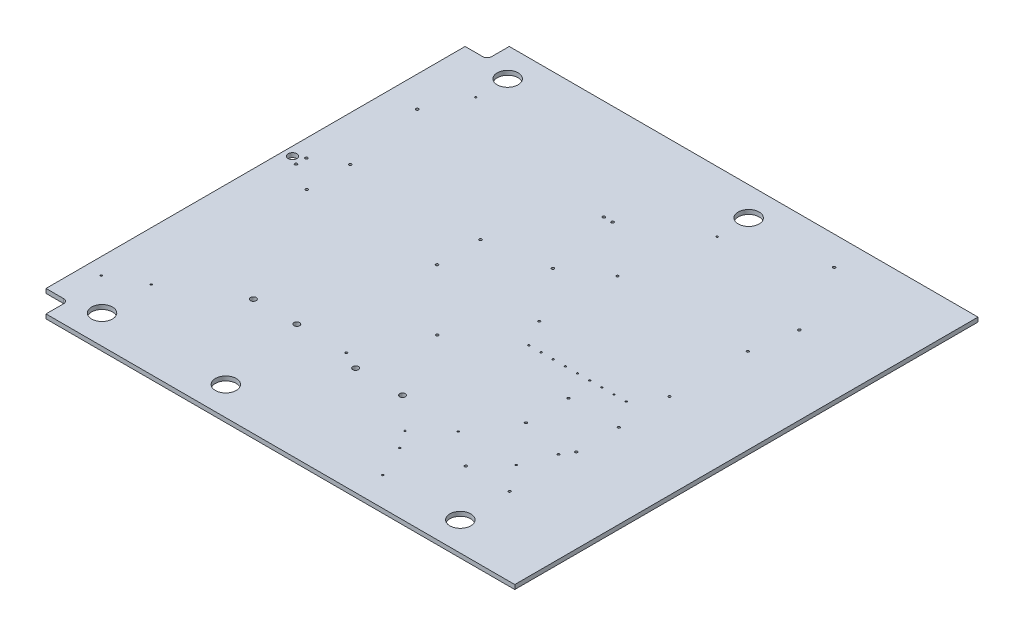
SolidWorks part; units mm, degrees
ref_plane "Front Plane" through (0, 0, 0) normal (0, 0, 1) x (1, 0, 0)
ref_plane "Top Plane" through (0, 0, 0) normal (0, 1, 0) x (1, 0, 0)
ref_plane "Right Plane" through (0, 0, 0) normal (1, 0, 0) x (0, 0, -1)
sketch "Sketch1" plane through (0, 0, 0) normal (1, 0, 0) x (0, 0, -1)
  line L0 (0, 0) -> (-533.4, 0)
  line L1 (-533.4, 0) -> (-533.4, 5)
  line L2 (-533.4, 5) -> (0, 5)
  line L6 (0, 5) -> (0, 0)
  dimension "D1" = 533.4
extrude "Boss-Extrude1" add sketch "Sketch1" along normal blind 565.15
sketch "BotthomHoles-Sketch2" plane through (0, 5, 0) normal (0, 1, 0) x (1, 0, 0)
  line L1 (565.15, 0) -> (565.15, -533.4) construction
  line L2 (565.15, -533.4) -> (0, -533.4) construction
  line L3 (565.15, 0) -> (0, 0) construction
  line L4 (0, 0) -> (0, -533.4) construction
  circle A0 centre (334.275, -33.175) radius 12
  circle A25 centre (199.275, -500.225) radius 12
  circle A26 centre (469.275, -500.225) radius 12
  circle A27 centre (56.75, -500.225) radius 12
  circle A28 centre (56.75, -33.175) radius 12
  dimension "D10" = 24
  dimension "D2" = 95.875
  dimension "D3" = 270
  dimension "D4" = 135
  dimension "D5" = 33.175
  dimension "D6" = 33.175
  dimension "D8" = 500.225
  dimension "D7" = 199.275
  dimension "D9" = 334.275
  dimension "D11" = 469.275
  dimension "D12" = 56.75
extrude "BottomStepperHoles-Cut-Extrude1" cut sketch "BotthomHoles-Sketch2" against normal through all
sketch "BottomPSUHolesSketch2" plane through (0, 5, 0) normal (0, 1, 0) x (1, 0, 0)
  line L0 (0, 0) -> (0, -533.4) construction
  line L1 (565.15, -533.4) -> (0, -533.4) construction
  line L2 (565.15, 0) -> (0, 0) construction
  circle A0 centre (201.5, -209.2) radius 1.5
  circle A1 centre (201.5, -259.2) radius 1.5
  circle A2 centre (51.5, -209.2) radius 1.5
  circle A3 centre (51.5, -259.2) radius 1.5
  circle A6 centre (180, -399.2) radius 3.25
  circle A7 centre (130, -399.2) radius 3.25
  circle A8 centre (257.75, -409.2) radius 3.25
  circle A9 centre (311.75, -409.2) radius 3.25
  dimension "D6" = 3
  dimension "D4" = 6.5
  dimension "D3" = 51.5
  dimension "D1" = 150
  dimension "D2" = 50
  dimension "D7" = 209.2
  dimension "D5" = 50
  dimension "D8" = 140
  dimension "D10" = 134.2
  dimension "D11" = 274.2
  dimension "D12" = 324.2
  dimension "D13" = 201.5
  dimension "D14" = 54
  dimension "D15" = 77.75
  dimension "D16" = 10
  dimension "D9" = 78.5
  dimension "D17" = 130
  dimension "D18" = 124.2
  dimension "D19" = 257.75
  dimension "D20" = 311.75
extrude "BottomPSUHolesCut-Extrude1" cut sketch "BottomPSUHolesSketch2" against normal through all
sketch "OctopusHolesSketch2" plane through (0, 5, 0) normal (0, 1, 0) x (1, 0, 0)
  line L0 (0, 0) -> (0, -533.4) construction
  line L1 (565.15, -533.4) -> (0, -533.4) construction
  circle A0 centre (316.75, -256.7) radius 1.35
  circle A1 centre (466.75, -256.7) radius 1.35
  circle A2 centre (316.75, -166.7) radius 1.35
  circle A3 centre (466.75, -166.7) radius 1.35
  dimension "D1" = 150
  dimension "D3" = 2.7
  dimension "D2" = 90
  dimension "D4" = 115.25
  dimension "D5" = 42.5
  dimension "D6" = 316.75
  dimension "D7" = 466.75
  dimension "D8" = 276.7
  dimension "D9" = 366.7
extrude "OctopusMountHolesCut-Extrude1" cut sketch "OctopusHolesSketch2" against normal through all
sketch "PowrCableGuideMountHolesSketch2" plane through (0, 5, 0) normal (0, 1, 0) x (1, 0, 0)
  line L0 (0, 0) -> (0, -533.4) construction
  line L1 (565.15, -533.4) -> (0, -533.4) construction
  circle A0 centre (271.75, -329.2) radius 1.5
  circle A1 centre (271.75, -196.2) radius 1.5
  dimension "D2" = 3
  dimension "D1" = 133
  dimension "D3" = 45
  dimension "D5" = 271.75
  dimension "D6" = 337.2
  dimension "D7" = 204.2
  dimension "D4" = 29.5
extrude "PowerCableGuideMountHolesCut-Extrude1" cut sketch "PowrCableGuideMountHolesSketch2" against normal through all
sketch "RPIHolesSketch2" plane through (0, 5, 0) normal (0, 1, 0) x (1, 0, 0)
  line L0 (0, 0) -> (0, -533.4) construction
  line L1 (565.15, -533.4) -> (0, -533.4) construction
  circle A4 centre (468.25, -316.7) radius 1.35
  circle A5 centre (468.25, -365.7) radius 1.35
  circle A6 centre (410.25, -316.7) radius 1.35
  circle A7 centre (410.25, -365.7) radius 1.35
  point P4 (282.575, -533.4)
  dimension "D7" = 2.7
  dimension "D1" = 58
  dimension "D2" = 49
  dimension "D3" = 60
  dimension "D4" = 1.5
  dimension "D5" = 410.25
  dimension "D6" = 468.25
  dimension "D8" = 167.7
  dimension "D9" = 216.7
extrude "RPIMountHolesCut-Extrude1" cut sketch "RPIHolesSketch2" against normal through all
sketch "DragChainAndCableGuideHolesSketch2" plane through (0, 5, 0) normal (0, 1, 0) x (1, 0, 0)
  line L3 (565.15, -533.4) -> (0, -533.4) construction
  line L9 (0, 0) -> (0, -533.4) construction
  circle A11 centre (260, -115.65) radius 1.5
  circle A12 centre (10, -234.2) radius 5
  circle A17 centre (475, -115.65) radius 1.5
  circle A18 centre (250, -115.65) radius 1.5
  circle A19 centre (35, -115.65) radius 1.5
  circle A20 centre (20, -240.2) radius 1.5
  circle A21 centre (20, -228.2) radius 1.5
  dimension "D17" = 3
  dimension "D10" = 10
  dimension "D26" = 3
  dimension "D13" = 299.2
  dimension "D15" = 260
  dimension "D5" = 215
  dimension "D16" = 8.25
  dimension "D18" = 475
  dimension "D19" = 215
  dimension "D20" = 10
  dimension "D22" = 35
  dimension "D23" = 250
  dimension "D6" = 25
  dimension "D11" = 10
  dimension "D21" = 6
  dimension "D24" = 6
  dimension "D25" = 20
  dimension "D3" = 417.75
extrude "CragChainAndCableGuideHolesCut-Extrude1" cut sketch "DragChainAndCableGuideHolesSketch2" against normal through all
sketch "Sketch2" plane through (0, 5, 0) normal (0, 1, 0) x (1, 0, 0)
  line L0 (565.15, -533.4) -> (0, -533.4) construction
  line L1 (0, 0) -> (0, -533.4) construction
  circle A0 centre (334.75, -286.7) radius 1
  circle A1 centre (348.75, -286.7) radius 1
  circle A2 centre (362.75, -286.7) radius 1
  circle A3 centre (376.75, -286.7) radius 1
  circle A4 centre (390.75, -286.7) radius 1
  circle A5 centre (404.75, -286.7) radius 1
  circle A6 centre (418.75, -286.7) radius 1
  circle A7 centre (432.75, -286.7) radius 1
  circle A8 centre (446.75, -286.7) radius 1
  dimension "D10" = 14
  dimension "D11" = 2
  dimension "D1" = 18
  dimension "D2" = 14
  dimension "D3" = 14
  dimension "D4" = 14
  dimension "D5" = 14
  dimension "D6" = 14
  dimension "D7" = 14
  dimension "D8" = 14
  dimension "D9" = 30
  dimension "D12" = 246.7
  dimension "D13" = 334.75
extrude "OctopusRouting holesCut-Extrude1" cut sketch "Sketch2" against normal through all
sketch "PiPowerAndSSRControlSketch3" plane through (0, 5, 0) normal (0, 1, 0) x (1, 0, 0)
  line L0 (565.15, -533.4) -> (0, -533.4) construction
  line L1 (0, 0) -> (0, -533.4) construction
  line L2 (565.15, -533.4) -> (0, -533.4) construction
  circle A10 centre (237, -399.2) radius 1.25
  circle A11 centre (460.5, -378.4) radius 1.25
  dimension "D16" = 134.2
  dimension "D18" = 237
  dimension "D19" = 460.5
  dimension "D20" = 155
extrude "PiPowerAndSSRControlCuts-Extrude1" cut sketch "PiPowerAndSSRControlSketch3" against normal through all
sketch "CornerCableKnotchesSketch4" plane through (0, 5, 0) normal (0, 1, 0) x (1, 0, 0)
  line L0 (0, -25.4) -> (20.4, -25.4)
  line L1 (25.4, 0) -> (25.4, -20.4)
  line L2 (565.15, 0) -> (0, 0) construction
  line L3 (0, -25.4) -> (0, 0)
  line L4 (0, 0) -> (0, -533.4) construction
  line L5 (0, 0) -> (25.4, 0)
  line L6 (0, -508) -> (20.4, -508)
  line L7 (25.4, -513) -> (25.4, -533.4)
  line L8 (565.15, -533.4) -> (0, -533.4) construction
  line L9 (0, -508) -> (0, -533.4)
  line L10 (0, -533.4) -> (25.4, -533.4)
  arc A0 (20.4, -25.4) -> (25.4, -20.4) centre (20.4, -20.4) ccw
  arc A1 (25.4, -513) -> (20.4, -508) centre (20.4, -513) ccw
  circle A2 centre (25, -115.65) radius 5 construction
  dimension "D2" = 10
  dimension "D1" = 25.4
extrude "CornerCableKnotchCut-Extrude1" cut sketch "CornerCableKnotchesSketch4" against normal through all
sketch "Z1 pathsSketch4" plane through (0, 5, 0) normal (0, 1, 0) x (1, 0, 0)
  line L2 (0, -25.4) -> (0, -508) construction
  line L3 (565.15, -533.4) -> (25.4, -533.4) construction
  circle A0 centre (432.75, -33.175) radius 1.5
  circle A1 centre (475, -115.65) radius 1.5 construction
  dimension "D1" = 432.75
  dimension "D2" = 500.225
extrude "Z1 patgsCut-Extrude1" cut sketch "Z1 pathsSketch4" against normal through all
sketch "Z2PathsSketch5" plane through (0, 5, 0) normal (0, 1, 0) x (1, 0, 0)
  line L0 (565.15, -533.4) -> (25.4, -533.4) construction
  line L1 (0, -25.4) -> (0, -508) construction
  circle A0 centre (380, -500.225) radius 1
  circle A1 centre (380, -413.4) radius 1
  circle A2 centre (446.75, -413.4) radius 1
  circle A3 centre (446.75, -286.7) radius 1 construction
  dimension "D1" = 33.175
  dimension "D2" = 120
  dimension "D3" = 380
  dimension "D4" = 446.75
extrude "Z2PathsCut-Extrude2" cut sketch "Z2PathsSketch5" against normal through all
sketch "ZPathsSketch4" plane through (0, 5, 0) normal (0, 1, 0) x (1, 0, 0)
  line L0 (565.15, -533.4) -> (25.4, -533.4) construction
  line L1 (0, -25.4) -> (0, -508) construction
  circle A0 centre (469.275, -443.4) radius 1.35
  circle A1 centre (418.75, -443.4) radius 1.35
  circle A2 centre (410.25, -365.7) radius 1.35 construction
  dimension "D1" = 90
  dimension "D2" = 469.275
  dimension "D3" = 418.75
extrude "ZPathsCut-Extrude1" cut sketch "ZPathsSketch4" against normal through all
sketch "LeftGantryAndExtruderPathsSketch4" plane through (0, 5, 0) normal (0, 1, 0) x (1, 0, 0)
  line L0 (565.15, -533.4) -> (25.4, -533.4) construction
  line L1 (0, -25.4) -> (0, -508) construction
  circle A0 centre (348.75, -443.4) radius 1
  circle A1 centre (362.75, -463.4) radius 1
  circle A2 centre (334.75, -286.7) radius 1 construction
  circle A3 centre (56.75, -443.4) radius 1
  circle A4 centre (19, -463.4) radius 1
  dimension "D1" = 70
  dimension "D2" = 90
  dimension "D3" = 56.75
  dimension "D4" = 19
  dimension "D5" = 348.75
  dimension "D6" = 362.75
extrude "LeftGantryAndExtruderPathsCut-Extrude1" cut sketch "LeftGantryAndExtruderPathsSketch4" against normal through all
sketch "RightGantryPathsSketch5" plane through (0, 5, 0) normal (0, 1, 0) x (1, 0, 0)
  line L0 (565.15, -533.4) -> (25.4, -533.4) construction
  line L1 (0, -25.4) -> (0, -508) construction
  circle A0 centre (334.75, -70) radius 1
  circle A1 centre (334.75, -286.7) radius 1 construction
  circle A2 centre (56.75, -70) radius 1
  dimension "D1" = 463.4
  dimension "D2" = 56.75
  dimension "D3" = 334.75
extrude "RightGantryPathsCut-Extrude2" cut sketch "RightGantryPathsSketch5" against normal through all
equation "\"RailThickness\"= .125in'Spec"
equation "\"Nema17MountStepperHoleDiameter\"= 24mm'Spec"
equation "\"SideRailLength\"= 21.75in"
equation "\"D10@BotthomHoles-Sketch2\" = \"Nema17MountStepperHoleDiameter\""
equation "\"D1@Boss-Extrude1\"=\"LowerEnclosureLength\""
equation "\"BedLength\"= \"BuildPlateLength\""
equation "\"DistanceBetweenFrontToBackStepperHoles\"= \"BedLength\" - \"BuildPlateStandoffHolesDistanceFromFrontOrBackSide\" * 2'Equals 270"
equation "\"LowerEnclosureThickness\"= 5mm"
equation "\"FrontOrBackRailLength\"= 20.5in"
equation "\"D1@Sketch1\"=\"LowerEncloseWidth\""
equation "\"D2@Sketch1\"=\"LowerEnclosureThickness\""
equation "\"24VPSUMountingHolesShortDistanceBetween\"= 50mm'Yours may differ"
equation "\"24VPSUMountingHolesLongDistanceBetween\"= 150mm'Yours may differ"
equation "\"24VPSUMountingHoleOffsetFromEitherSide\"= 32.5mm'Yours may differ"
equation "\"24VPSUMountingHoleDiameter\"= 3mm'Yours may differ"
equation "\"D6@BottomPSUHolesSketch2\" = \"24VPSUMountingHoleDiameter\""
equation "\"RPi4BoardMountingHoleDiameter\"= 2.7mm'Spec"
equation "\"OctopusV1.1BoardMountingHoleOffsetFromAllEdges\"= 5mm'Spec"
equation "\"OctopusV1.1BoardMountingHoleLengthDistanceBetween\"= 150mm'Spec"
equation "\"OctopusV1.1BoardMountingHoleWidthDistanceBetween\"= 90mm'Spec"
equation "\"D7@RPIHolesSketch2\" = \"RPi4BoardMountingHoleDiameter\""
equation "\"RPi4BoardMountingHoleLengthDistanceBetween\"= 58mm'Spec"
equation "\"OctopusV1.1BoardMountingHoleDiameter\"= 2.7mm'Spec"
equation "\"CWD4890MountingHoleWidthDistance\"= 50mm'Spec"
equation "\"24VPSULength\"= 213mm'Spec"
equation "\"D3@OctopusHolesSketch2\"=\"OctopusV1.1BoardMountingHoleDiameter\""
equation "\"24VPSUMountingHoleOffsetFromFront\"= 32.5mm"
equation "\"DistanceBetween24VPSUAndOctopus\"= \"24VPSUMountingHoleOffsetFromFront\" + \"OctopusV1.1BoardMountingHoleOffsetFromAllEdges\" + 77.75'77.75mm gives 10mm before and after 60mm cable guide"
equation "\"GapBetweenVerticalSupportsAndRails\"= \"RailThickness\" * 2"
equation "\"LowerEncloseWidth\"= \"FrontOrBackRailLength\" + \"GapBetweenVerticalSupportsAndRails\" * 2"
equation "\"Nema17MountStepperHoleFromBack\"= 30mm"
equation "\"D2@BotthomHoles-Sketch2\"=\"DistanceFromFrontSideToFirstLeftStepperHoleMountYSValue\" + \"Nema17StepperMountSlotDistance\"/2 + \"GapBetweenVerticalSupportsAndRails\""
equation "\"D3@BotthomHoles-Sketch2\"=\"DistanceBetweenFrontToBackStepperHoles\""
equation "\"D4@BotthomHoles-Sketch2\"=\"DistanceBetweenFrontToBackStepperHoles\"/2"
equation "\"D5@BotthomHoles-Sketch2\"=\"Nema17MountStepperHoleFromBack\" + \"RailThickness\""
equation "\"D6@BotthomHoles-Sketch2\"=\"Nema17MountStepperHoleFromBack\" + \"RailThickness\""
equation "\"LowerEnclosureLength\"= \"SideRailLength\" + \"GapBetweenVerticalSupportsAndRails\" * 2"
equation "\"DistanceFromFrontSideToFirstLeftStepperHoleMountYSValue\"= 74.025mm"
equation "\"BuildPlateStandoffHolesDistanceFromFrontOrBackSide\"= 41mm"
equation "\"BuildPlateLength\"= 352mm'Spec"
equation "\"D1@BottomPSUHolesSketch2\"=\"24VPSUMountingHolesLongDistanceBetween\""
equation "\"D2@BottomPSUHolesSketch2\"=\"24VPSUMountingHolesShortDistanceBetween\""
equation "\"24VPSUOffsetFromBack\"= ( \"24VPSULength\" - \"24VPSUMountingHolesLongDistanceBetween\" ) / 2 + 20mm"
equation "\"24VPSUOffsetFromRightSide\"= ( \"LowerEncloseWidth\" - \"24VPSUWidth\" ) / 2"
equation "\"24VPSUWidth\"= 115mm'Yours may differ"
equation "\"D3@BottomPSUHolesSketch2\"=\"24VPSUOffsetFromBack\""
equation "\"D1@OctopusHolesSketch2\"=\"OctopusV1.1BoardMountingHoleLengthDistanceBetween\""
equation "\"D2@OctopusHolesSketch2\"=\"OctopusV1.1BoardMountingHoleWidthDistanceBetween\""
equation "\"D4@OctopusHolesSketch2\" = \"DistanceBetween24VPSUAndOctopus\""
equation "\"RPI4BoardMountingHoleWidthDistanceBetween\"= 49mm"
equation "\"D7@BottomPSUHolesSketch2\"=\"24VPSUOffsetFromRightSide\""
equation "\"D1@RPIHolesSketch2\"=\"RPi4BoardMountingHoleLengthDistanceBetween\""
equation "\"D2@RPIHolesSketch2\"=\"RPI4BoardMountingHoleWidthDistanceBetween\""
equation "\"D5@BottomPSUHolesSketch2\"=\"CWD4890MountingHoleWidthDistance\""
equation "\"OctopusV1.1ToPSUNegTerminalOffset\"= \"24VPSUNegTerminalOffsetFromSide\" - \"24VPSUMountingHoleOffsetFromEitherSide\" + \"OctopusV1.1NegTerminalOffsetFromSide\" + \"OctopusV1.1BoardMountingHoleOffsetFromAllEdges\""
equation "\"24VPSUNegTerminalOffsetFromSide\"= 50.5mm"
equation "\"OctopusV1.1NegTerminalOffsetFromSide\"= 19.5mm"
equation "\"D5@OctopusHolesSketch2\" = \"OctopusV1.1ToPSUNegTerminalOffset\""
equation "\"PowerCableGuideMountingHoleDistanceBetweenValue\"=133"
equation "\"D1@PowrCableGuideMountHolesSketch2\" = \"PowerCableGuideMountingHoleDistanceBetweenValue\""
equation "\"D2@PowrCableGuideMountHolesSketch2\" = \"24VPSUMountingHoleDiameter\""
equation "\"RCNUNMountingHoleWidthDistance\"= 54mm"
equation "\"D14@BottomPSUHolesSketch2\"=\"RCNUNMountingHoleWidthDistance\""
equation "\"OctopusToPowerCableGuideOffset\"= 29.5mm'This asligned perfectly"
equation "\"D4@PowrCableGuideMountHolesSketch2\"=\"OctopusToPowerCableGuideOffset\""
equation "\"VSWidth\"= 1.25in'Spec"
equation "\"D1@CornerCableKnotchesSketch4\" = \"VSWidth\" - \"RailThickness\" * 2"
equation "\"Nema17StepperMountSlotDistance\"= 31mm'Spec"
equation "\"D6@DragChainAndCableGuideHolesSketch2\" = \"24VPSUMountingHolesShortDistanceBetween\" / 2"
equation "\"DistanceFromBackToFirstGantryStepperHole\"= \"VSWidth\" - \"RailThickness\" + ( \"Nema17MountWidth\" - \"Nema17StepperMountSlotDistance\" ) / 2 - \"GapBetweenVerticalSupportsAndRails\" / 2'Equals 34.9. Push Gantry stepper as far back as possible"
equation "\"Nema17MountWidth\"= 50mm"
equation "\"D12@BotthomHoles-Sketch2\"=\"DistanceFromBackToFirstGantryStepperHole\" + \"GapBetweenVerticalSupportsAndRails\" + \"Nema17StepperMountSlotDistance\"/2"
